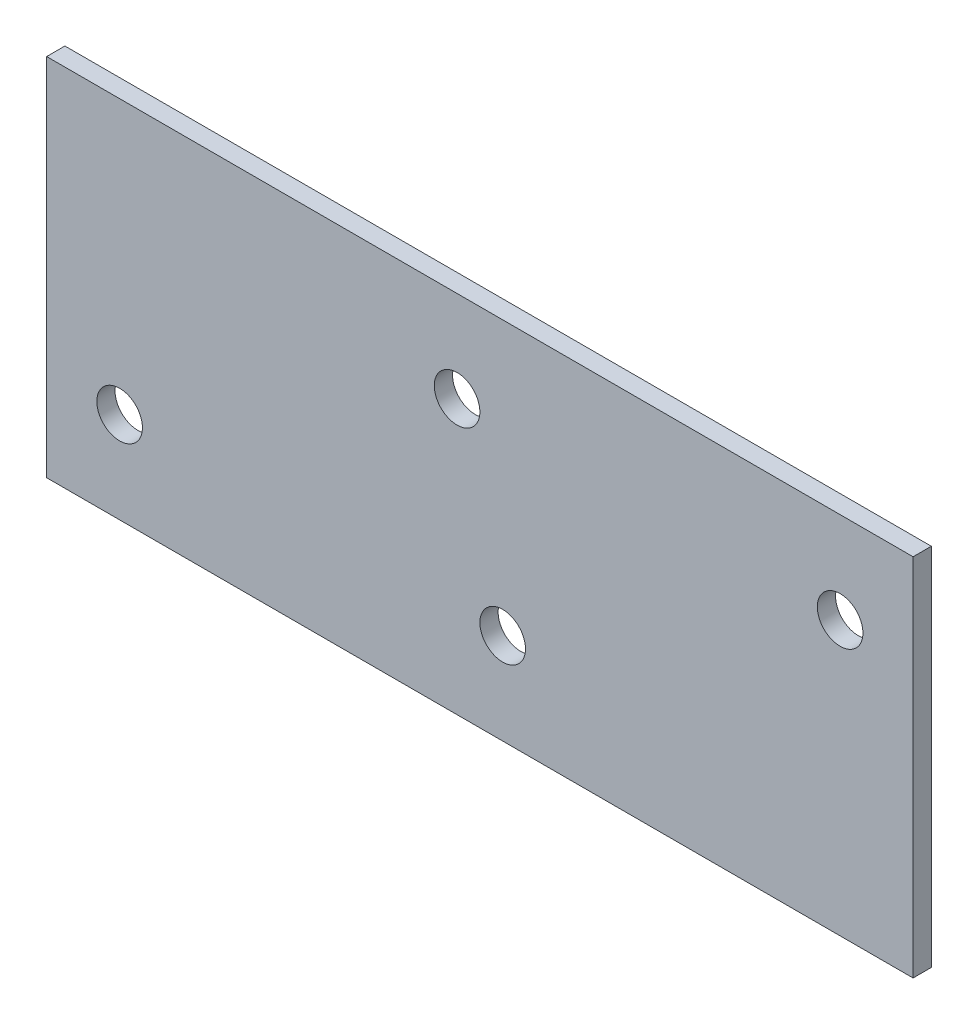
SolidWorks part; units mm, degrees
ref_plane "前视基准面" through (0, 0, 0) normal (0, 0, 1) x (1, 0, 0)
ref_plane "上视基准面" through (0, 0, 0) normal (0, 1, 0) x (1, 0, 0)
ref_plane "右视基准面" through (0, 0, 0) normal (1, 0, 0) x (0, 0, -1)
sketch "草图1" plane through (0, 0, 0) normal (0, 0, 1) x (1, 0, 0)
  line L0 (-37.5, 0) -> (57.5, 0) construction
  line L1 (57.5, 20) -> (-37.5, 20)
  line L2 (57.5, 20) -> (57.5, -20)
  line L3 (57.5, -20) -> (-37.5, -20)
  line L4 (-37.5, 20) -> (-37.5, -20)
  circle A1 centre (7.5, 10) radius 2.5
  circle A2 centre (12.5, -10) radius 2.5
  circle A4 centre (-29.5, -10) radius 2.5
  circle A7 centre (49.5, 10) radius 2.5
  point P0 (0, 0)
  point P8 (0, 0)
  point P9 (0, 0)
  point P21 (12.5, -10)
  dimension "D5" = 8
  dimension "D1" = 40
  dimension "D2" = 95
  dimension "D3" = 42
  dimension "D4" = 8
  dimension "D6" = 42
extrude "凸台-拉伸1" add sketch "草图1" along normal blind 2
